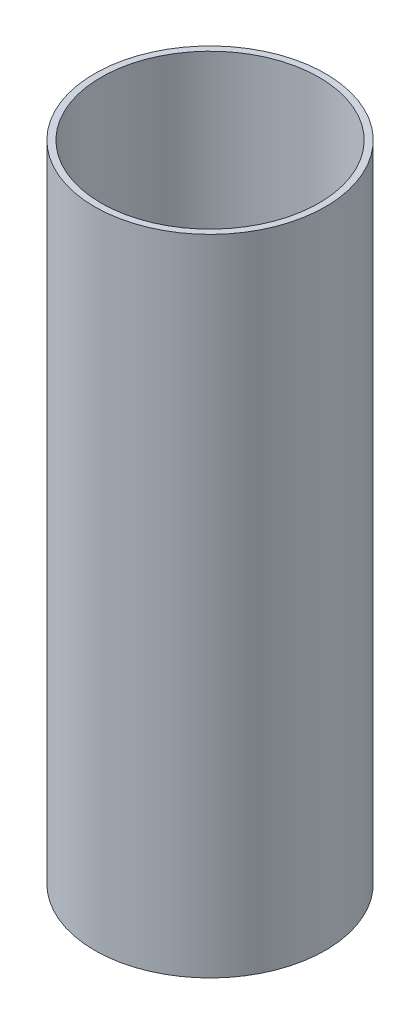
SolidWorks part; units mm, degrees
material "Polycarbonate-Zelux M"
ref_plane "Front Plane" through (0, 0, 0) normal (0, 0, 1) x (1, 0, 0)
ref_plane "Top Plane" through (0, 0, 0) normal (0, 1, 0) x (1, 0, 0)
ref_plane "Right Plane" through (0, 0, 0) normal (1, 0, 0) x (0, 0, -1)
sketch "Sketch1" plane through (0, 0, 0) normal (0, 1, 0) x (1, 0, 0)
  line L0 (0, 0) -> (26.9875, 0) construction
  line L1 (26.9875, 0) -> (28.575, 0) construction
  circle A0 centre (0, 0) radius 26.9875
  circle A1 centre (0, 0) radius 28.575
  dimension "D1" = 57.15
  dimension "D2" = 1.5875
extrude "Boss-Extrude1" add sketch "Sketch1" along normal blind 159.4485
sketch "Sketch3" [suppressed] plane through (0, 166.624, 0) normal (0, 1, 0) x (1, 0, 0)
  circle A0 centre (0, 0) radius 28.575
  circle A1 centre (0, 0) radius 28.575 construction
extrude "Cut-Extrude1" [suppressed] cut sketch "Sketch3" against normal offset from surface (44.3865 mm away) 122.2375
